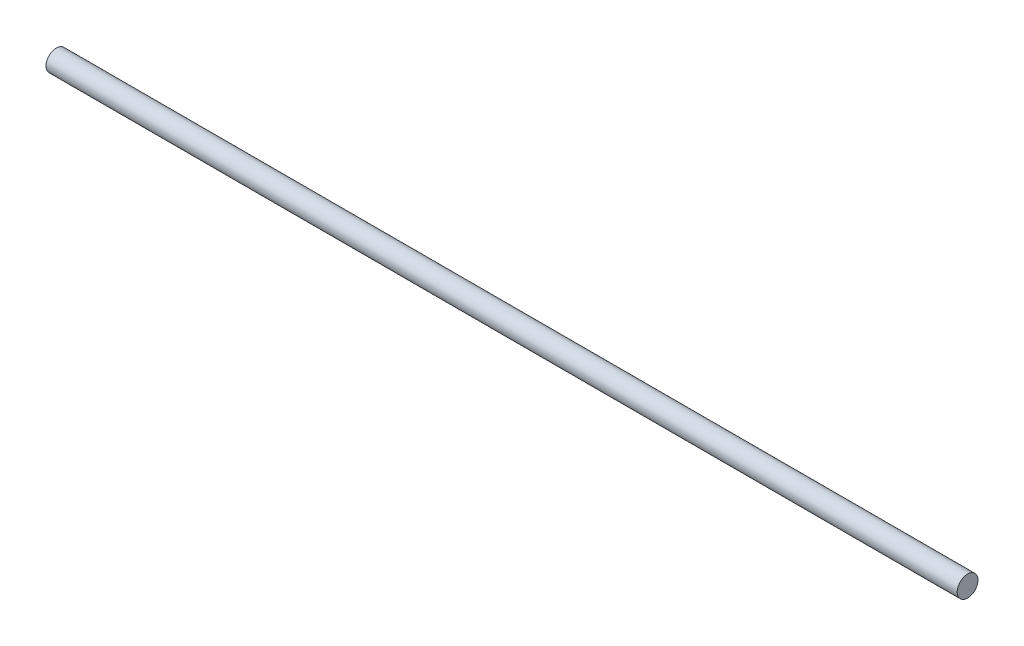
SolidWorks part; units mm, degrees
material "1060 合金"
ref_plane "前视基准面" through (0, 0, 0) normal (0, 0, 1) x (1, 0, 0)
ref_plane "上视基准面" through (0, 0, 0) normal (0, 1, 0) x (1, 0, 0)
ref_plane "右视基准面" through (0, 0, 0) normal (1, 0, 0) x (0, 0, -1)
other "Configuration Table"
sketch "草图1" plane through (0, 0, 0) normal (1, 0, 0) x (0, 0, -1)
  circle A0 centre (0, 0) radius 4
  dimension "D1" = 8
extrude "凸台-拉伸1" add sketch "草图1" along normal blind 350
